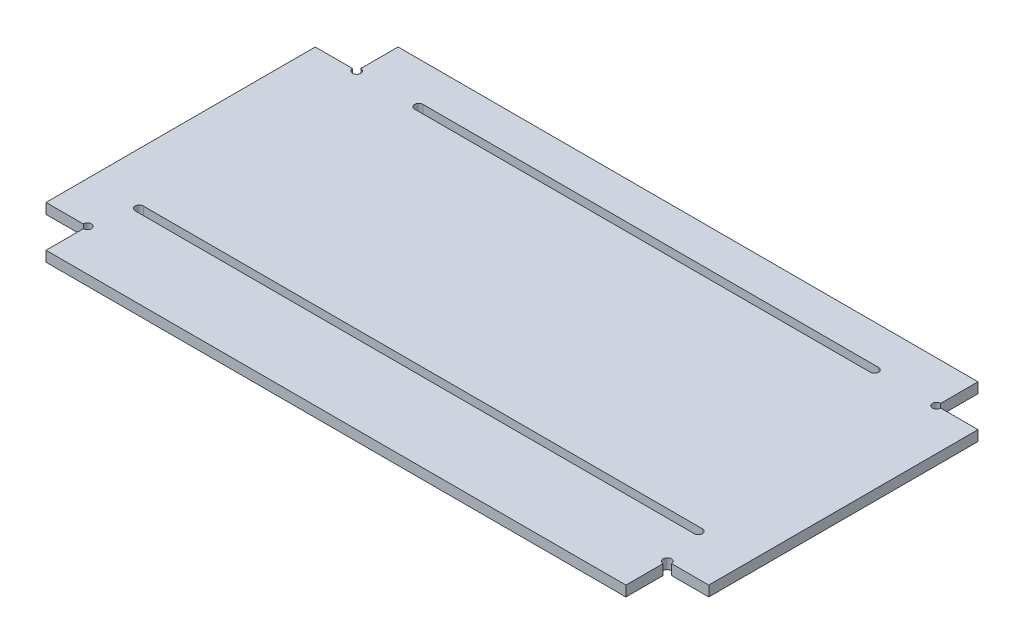
SolidWorks part; units mm, degrees
material "Perspex (TM) GS Acrylic Cast Sheet"
ref_plane "Ebene vorne" through (0, 0, 0) normal (0, 0, 1) x (1, 0, 0)
ref_plane "Ebene oben" through (0, 0, 0) normal (0, 1, 0) x (1, 0, 0)
ref_plane "Ebene rechts" through (0, 0, 0) normal (1, 0, 0) x (0, 0, -1)
sketch "Skizze1" plane through (0, 0, 0) normal (0, 1, 0) x (1, 0, 0)
  line L1 (-160, 85) -> (160, 85)
  line L2 (-160, 85) -> (-160, -85)
  line L3 (-160, -85) -> (160, -85)
  line L4 (160, 85) -> (160, -85)
  line L5 (-160, 85) -> (160, -85) construction
  line L6 (-160, -85) -> (160, 85) construction
  point P0 (0, 0)
  dimension "D1" = 170
  dimension "D2" = 320
extrude "Aufsatz-Linear austragen1" add sketch "Skizze1" along normal blind 5
sketch "Skizze2" plane through (0, 5, 0) normal (0, 1, 0) x (1, 0, 0)
  line L1 (-160, 85) -> (-140, 85)
  line L2 (-160, 85) -> (-160, 65)
  line L3 (-160, 65) -> (-140, 65)
  line L4 (-140, 85) -> (-140, 65)
  line L5 (-160, 85) -> (-140, 65) construction
  line L6 (-160, 65) -> (-140, 85) construction
  line L7 (140, -65) -> (-140, -65) construction
  line L8 (140, -65) -> (140, 65) construction
  line L9 (140, 65) -> (-140, 65) construction
  line L10 (-140, -65) -> (-140, 65) construction
  line L11 (140, -65) -> (-140, 65) construction
  line L12 (140, 65) -> (-140, -65) construction
  line L13 (160, 85) -> (140, 85)
  line L14 (160, 85) -> (160, 65)
  line L15 (160, 65) -> (140, 65)
  line L16 (140, 85) -> (140, 65)
  line L17 (160, 85) -> (140, 65) construction
  line L18 (160, 65) -> (140, 85) construction
  line L19 (160, -85) -> (140, -85)
  line L20 (160, -85) -> (160, -65)
  line L21 (160, -65) -> (140, -65)
  line L22 (140, -85) -> (140, -65)
  line L23 (160, -85) -> (140, -65) construction
  line L24 (160, -65) -> (140, -85) construction
  line L25 (-160, -85) -> (-140, -85)
  line L26 (-160, -85) -> (-160, -65)
  line L27 (-160, -65) -> (-140, -65)
  line L28 (-140, -85) -> (-140, -65)
  line L29 (-160, -85) -> (-140, -65) construction
  line L30 (-160, -65) -> (-140, -85) construction
  point P4 (-150, 75)
  point P6 (0, 0)
  point P15 (150, 75)
  point P20 (150, -75)
  point P25 (-150, -75)
  dimension "D1" = 20
extrude "Schnitt-Linear austragen1" cut sketch "Skizze2" against normal through all
sketch "Skizze3" plane through (0, 5, 0) normal (0, 1, 0) x (1, 0, 0)
  line L0 (-110, 65) -> (110, 65) construction
  line L1 (-110, 67) -> (110, 67)
  line L2 (-110, 63) -> (110, 63)
  line L3 (140, 85) -> (-140, 85) construction
  line L4 (0, 0) -> (0, 50000) construction
  line L5 (-135, -45) -> (135, -45) construction
  line L6 (-135, -43) -> (135, -43)
  line L7 (-135, -47) -> (135, -47)
  line L8 (-140, -65) -> (-160, -65) construction
  arc A0 (-110, 67) -> (-110, 63) centre (-110, 65) ccw
  arc A1 (110, 63) -> (110, 67) centre (110, 65) ccw
  arc A2 (-135, -43) -> (-135, -47) centre (-135, -45) ccw
  arc A3 (135, -47) -> (135, -43) centre (135, -45) ccw
  point P2 (0, 65)
  point P12 (0, -45)
  point P21 (0, 0)
  dimension "D1" = 20
  dimension "D2" = 220
  dimension "D3" = 4
  dimension "D4" = 20
  dimension "D5" = 270
  dimension "D6" = 4
extrude "Schnitt-Linear austragen2" cut sketch "Skizze3" against normal through all
sketch "Skizze4" plane through (0, 5, 0) normal (0, 1, 0) x (1, 0, 0)
  circle A0 centre (-140, 65) radius 2
  circle A1 centre (-140, -65) radius 2
  circle A2 centre (140, -65) radius 2
  circle A3 centre (140, 65) radius 2
  dimension "D1" = 4
extrude "Schnitt-Linear austragen3" cut sketch "Skizze4" against normal through all
